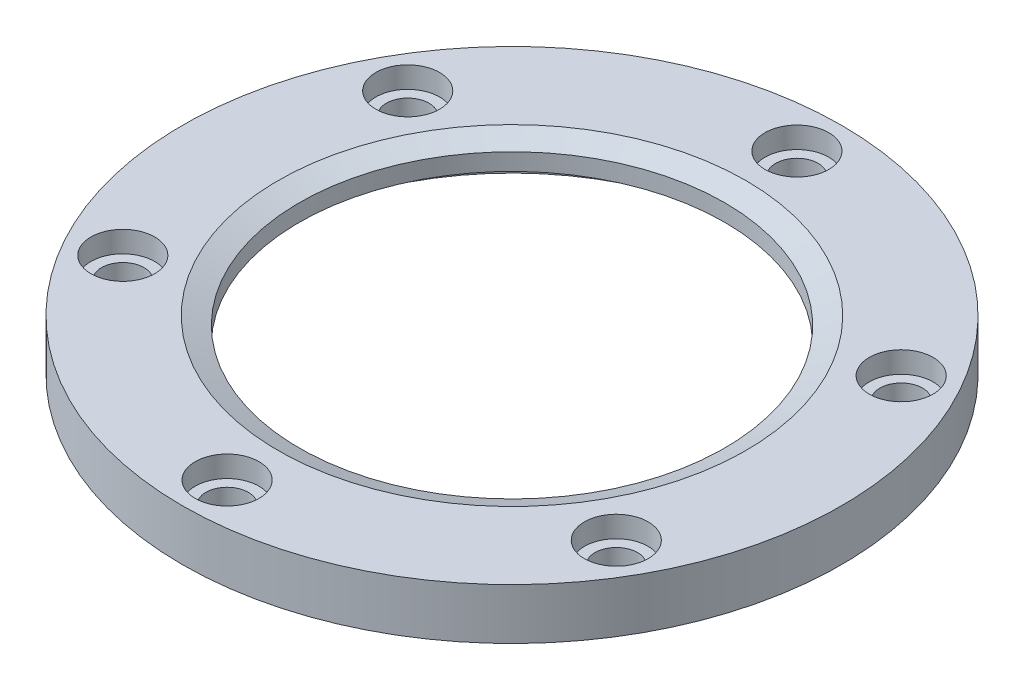
SolidWorks part; units mm, degrees
material "1060 合金"
ref_plane "前视基准面" through (0, 0, 0) normal (0, 0, 1) x (1, 0, 0)
ref_plane "上视基准面" through (0, 0, 0) normal (0, 1, 0) x (1, 0, 0)
ref_plane "右视基准面" through (0, 0, 0) normal (1, 0, 0) x (0, 0, -1)
sketch "草图1" plane through (0, 0, 0) normal (0, 1, 0) x (1, 0, 0)
  circle A0 centre (0, 0) radius 77.5
  dimension "D1" = 155
extrude "D155 观察窗外盖" add sketch "草图1" along normal blind 12
sketch "草图2" plane through (0, 0, 0) normal (0, 0, 1) x (1, 0, 0)
  line L0 (50, 10) -> (55, 12)
  line L1 (0, 0) -> (50, 0)
  line L2 (0, 0) -> (0, 12)
  line L3 (0, 12) -> (50, 12)
  line L4 (50, 0) -> (50, 10)
  line L5 (50, 12) -> (55, 12)
  dimension "D1" = 12
  dimension "D2" = 50
  dimension "D3" = 2
  dimension "D4" = 5
revolve "D100 内径切除" cut sketch "草图2" angle 360 about L2
sketch "草图3" plane through (0, 0, 0) normal (0, -1, 0) x (1, 0, 0)
  circle A0 centre (0, 0) radius 58
  dimension "D1" = 116
extrude "D116*2 橡胶垫(外径)" cut sketch "草图3" against normal blind 6
hole_wizard "M10*6 柱形沉头孔" positions "草图5" profile "草图6" legacy end condition up to next
sketch "草图5" plane through (0, 12, 0) normal (0, 1, 0) x (1, 0, 0)
  point P0 (0, 67)
  dimension "D1" = 67
sketch "草图6" plane through (0, 12, -67) normal (1, 0, 0) x (0, 0, 1)
  line L0 (0, 0) -> (0, 12.001)
  line L1 (0, 12.001) -> (5, 12.001)
  line L3 (5, 12.001) -> (5, 5)
  line L4 (5, 5) -> (7.5, 5)
  line L5 (7.5, 5) -> (7.5, 0)
  line L7 (7.5, 0) -> (0, 0)
  line L11 (0, -6.35) -> (0, 107.95) construction
  dimension "通孔孔直径" = 10
  dimension "通孔孔深度" = 12.001
  dimension "柱形沉头孔直径" = 15
  dimension "柱形沉头孔深度" = 5
pattern_circular "M10*6 圆周阵列" count 6 over 360 about axis through (0, 0, 0) along (0, 1, 0) of "M10*6 柱形沉头孔"
